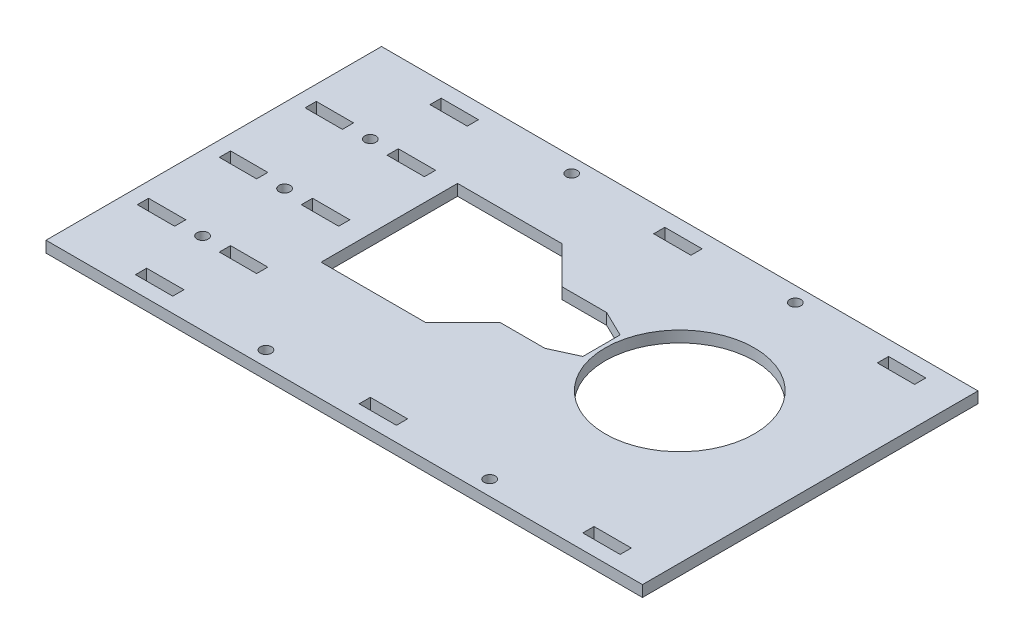
SolidWorks part; units mm, degrees
ref_plane "Front Plane" through (0, 0, 0) normal (0, 0, 1) x (1, 0, 0)
ref_plane "Top Plane" through (0, 0, 0) normal (0, 1, 0) x (1, 0, 0)
ref_plane "Right Plane" through (0, 0, 0) normal (1, 0, 0) x (0, 0, -1)
sketch "Sketch1" plane through (0, 0, 0) normal (0, 1, 0) x (1, 0, 0)
  line L0 (-118, 68.4) -> (-118, 31.8)
  line L1 (-160, 90) -> (0, 90)
  line L2 (-160, 90) -> (-160, 0)
  line L3 (-160, 0) -> (0, 0)
  line L4 (0, 90) -> (0, 0)
  line L10 (-118, 31.8) -> (-90, 31.8)
  line L11 (-90, 68.4) -> (-118, 68.4)
  line L12 (-68, 58.4) -> (-80, 58.4)
  line L13 (-80, 58.4) -> (-90, 68.4)
  line L14 (-68, 41.8) -> (-80, 41.8)
  line L16 (-61, 45) -> (-68, 41.8)
  line L18 (-61, 55) -> (-68, 58.4)
  line L19 (-90, 31.8) -> (-80, 41.8)
  line L20 (-61, 55) -> (-61, 45)
  line L21 (-160, 45) -> (0, 45) construction
  line L22 (-130, 83) -> (-130, 86)
  line L23 (-140, 4) -> (-140, 7)
  line L24 (-140, 7) -> (-130, 7)
  line L25 (-130, 7) -> (-130, 4)
  line L26 (-140, 86) -> (-130, 86)
  line L27 (-140, 83) -> (-130, 83)
  line L28 (-140, 86) -> (-140, 83)
  line L29 (-80, 4) -> (-80, 7)
  line L30 (-80, 7) -> (-70, 7)
  line L31 (-70, 7) -> (-70, 4)
  line L32 (-80, 86) -> (-80, 83)
  line L33 (-80, 83) -> (-70, 83)
  line L34 (-80, 86) -> (-70, 86)
  line L35 (-20, 4) -> (-20, 7)
  line L36 (-20, 7) -> (-10, 7)
  line L37 (-10, 7) -> (-10, 4)
  line L38 (-70, 83) -> (-70, 86)
  line L39 (-140, 4) -> (-130, 4)
  line L40 (-80, 4) -> (-70, 4)
  line L41 (-20, 4) -> (-10, 4)
  line L42 (-20, 86) -> (-20, 83)
  line L43 (-20, 86) -> (-10, 86)
  line L44 (-10, 83) -> (-10, 86)
  line L45 (-20, 83) -> (-10, 83)
  line L46 (-140, 83) -> (-140, 45) construction
  line L47 (-156, 68.5) -> (-156, 65.5)
  line L48 (-156, 65.5) -> (-146, 65.5)
  line L49 (-146, 65.5) -> (-146, 68.5)
  line L50 (-146, 68.5) -> (-156, 68.5)
  line L51 (-124, 68.5) -> (-124, 65.5)
  line L52 (-124, 65.5) -> (-134, 65.5)
  line L53 (-134, 68.5) -> (-124, 68.5)
  line L54 (-134, 65.5) -> (-134, 68.5)
  line L56 (-160, 55.5) -> (-118, 55.5) construction
  line L57 (-134, 45.5) -> (-134, 42.5)
  line L58 (-124, 42.5) -> (-124, 45.5)
  line L59 (-124, 45.5) -> (-134, 45.5)
  line L60 (-134, 42.5) -> (-124, 42.5)
  line L61 (-156, 42.5) -> (-156, 45.5)
  line L62 (-146, 42.5) -> (-156, 42.5)
  line L63 (-146, 45.5) -> (-146, 42.5)
  line L64 (-156, 45.5) -> (-146, 45.5)
  line L65 (-160, 33) -> (0, 33) construction
  line L66 (-156, 23.5) -> (-156, 20.5)
  line L67 (-156, 20.5) -> (-146, 20.5)
  line L68 (-146, 20.5) -> (-146, 23.5)
  line L69 (-146, 23.5) -> (-156, 23.5)
  line L70 (-134, 20.5) -> (-134, 23.5)
  line L71 (-124, 20.5) -> (-134, 20.5)
  line L72 (-124, 23.5) -> (-124, 20.5)
  line L73 (-134, 23.5) -> (-124, 23.5)
  circle A0 centre (-40, 50) radius 20
  circle A1 centre (-105, 4) radius 1.5
  circle A2 centre (-45, 4) radius 1.5
  circle A3 centre (-105, 86) radius 1.5
  circle A4 centre (-45, 86) radius 1.5
  circle A5 centre (-140, 67) radius 1.5
  circle A6 centre (-140, 44) radius 1.5
  circle A7 centre (-140, 22) radius 1.5
  point P20 (-61, 50)
  point P59 (-146, 67)
  point P79 (-156, 31.8)
  point P80 (-134, 44)
  point P86 (-134, 22)
  point P91 (-160, 31.8)
  point P92 (0, 0)
  dimension "D3" = 40
  dimension "D5" = 40
  dimension "D20" = 3
  dimension "D24" = 6
  dimension "D1" = 90
  dimension "D2" = 160
  dimension "D4" = 50
  dimension "D6" = 12
  dimension "D7" = 28
  dimension "D8" = 21
  dimension "D9" = 7
  dimension "D10" = 10
  dimension "D11" = 16.6
  dimension "D12" = 3.4
  dimension "D13" = 10
  dimension "D14" = 3
  dimension "D15" = 10
  dimension "D16" = 20
  dimension "D17" = 4
  dimension "D18" = 50
  dimension "D19" = 50
  dimension "D21" = 25
  dimension "D22" = 25
  dimension "D23" = 4
  dimension "D25" = 20
  dimension "D26" = 19
  dimension "D27" = 21.5
extrude "Boss-Extrude1" add sketch "Sketch1" along normal blind 3
